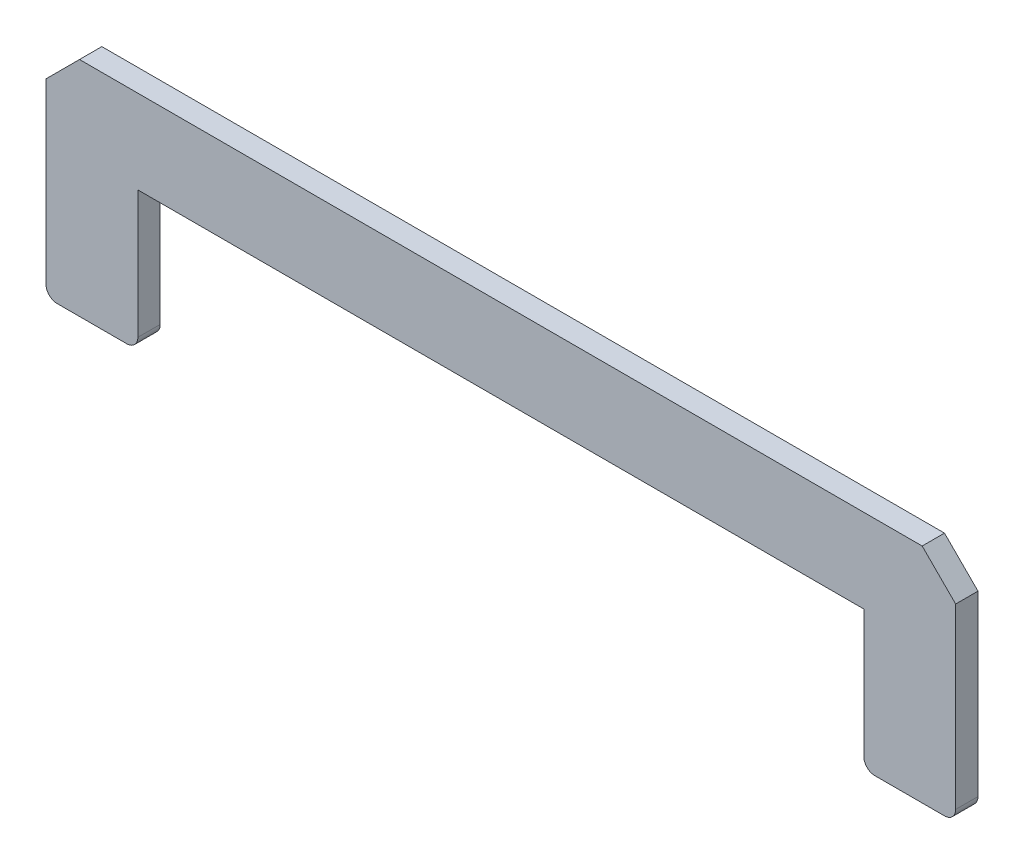
SolidWorks part; units mm, degrees
ref_plane "Front Plane" through (0, 0, 0) normal (0, 0, 1) x (1, 0, 0)
ref_plane "Top Plane" through (0, 0, 0) normal (0, 1, 0) x (1, 0, 0)
ref_plane "Right Plane" through (0, 0, 0) normal (1, 0, 0) x (0, 0, -1)
sketch "Sketch1" plane through (0, 0, 0) normal (0, 0, 1) x (1, 0, 0)
  line L0 (5.842, 0) -> (16.2941, 0)
  line L1 (16.2941, 0) -> (16.2941, 33.782)
  line L2 (16.2941, 33.782) -> (98.8441, 33.782)
  line L3 (98.8441, 33.782) -> (98.8441, 0)
  line L4 (98.8441, 0) -> (109.2962, 0)
  line L5 (109.2962, 0) -> (109.2962, 2.794)
  line L6 (109.2962, 2.794) -> (115.1382, 2.794)
  line L7 (115.1382, 2.794) -> (115.1382, 33.782)
  line L8 (115.1382, 33.782) -> (109.2962, 33.782)
  line L9 (109.2962, 33.782) -> (109.2962, 43.307)
  line L10 (109.2962, 43.307) -> (5.842, 43.307)
  line L11 (5.842, 43.307) -> (5.842, 33.782)
  line L12 (5.842, 33.782) -> (0, 33.782)
  line L13 (0, 33.782) -> (0, 2.794)
  line L14 (0, 2.794) -> (5.842, 2.794)
  line L15 (5.842, 2.794) -> (5.842, 0)
  dimension "D1" = 115.1382
  dimension "D2" = 30.988
  dimension "D3" = 30.988
  dimension "D4" = 9.525
  dimension "D5" = 9.525
  dimension "D6" = 2.794
  dimension "D7" = 16.2941
  dimension "D8" = 5.842
  dimension "D9" = 9.525
  dimension "D10" = 5.842
  dimension "D11" = 5.842
  dimension "D12" = 5.842
  dimension "D13" = 16.2941
extrude "Boss-Extrude1" add sketch "Sketch1" along normal blind 2.54
chamfer "Chamfer1" distance 3.81 angle 45 2 edges at (109.2962, 43.307, 1.27) (5.842, 43.307, 1.27)
sketch "Sketch2" plane through (0, 0, 2.54) normal (0, 0, 1) x (1, 0, 0)
  line L1 (0, 33.782) -> (5.842, 33.782)
  line L2 (0, 33.782) -> (0, -3.0988)
  line L3 (0, -3.0988) -> (16.2941, -3.0988)
  line L4 (5.842, 33.782) -> (5.842, 17.9952)
  line L5 (5.842, 17.9952) -> (16.2941, 17.9952)
  line L6 (16.2941, 0) -> (16.2941, 33.782) construction
  line L7 (16.2941, 17.9952) -> (16.2941, -3.0988)
extrude "Cut-Extrude1" cut sketch "Sketch2" against normal through all
sketch "Sketch3" plane through (0, 0, 2.54) normal (0, 0, 1) x (1, 0, 0)
  line L0 (109.2962, 33.782) -> (115.1382, 33.782)
  line L1 (115.1382, 33.782) -> (115.1382, -2.2244)
  line L2 (115.1382, -2.2244) -> (98.8441, 0)
  line L3 (98.8441, 0) -> (42.8675, 17.9952)
  line L4 (42.8675, 17.9952) -> (109.2962, 17.9952)
  line L5 (109.2962, 17.9952) -> (109.2962, 33.782)
extrude "Cut-Extrude2" cut sketch "Sketch3" against normal through all
fillet "Fillet1" radius 1.27 4 edges at (98.8441, 17.9952, 1.27) (16.2941, 17.9952, 1.27) (109.2962, 17.9952, 1.27) (5.842, 17.9952, 1.27)
